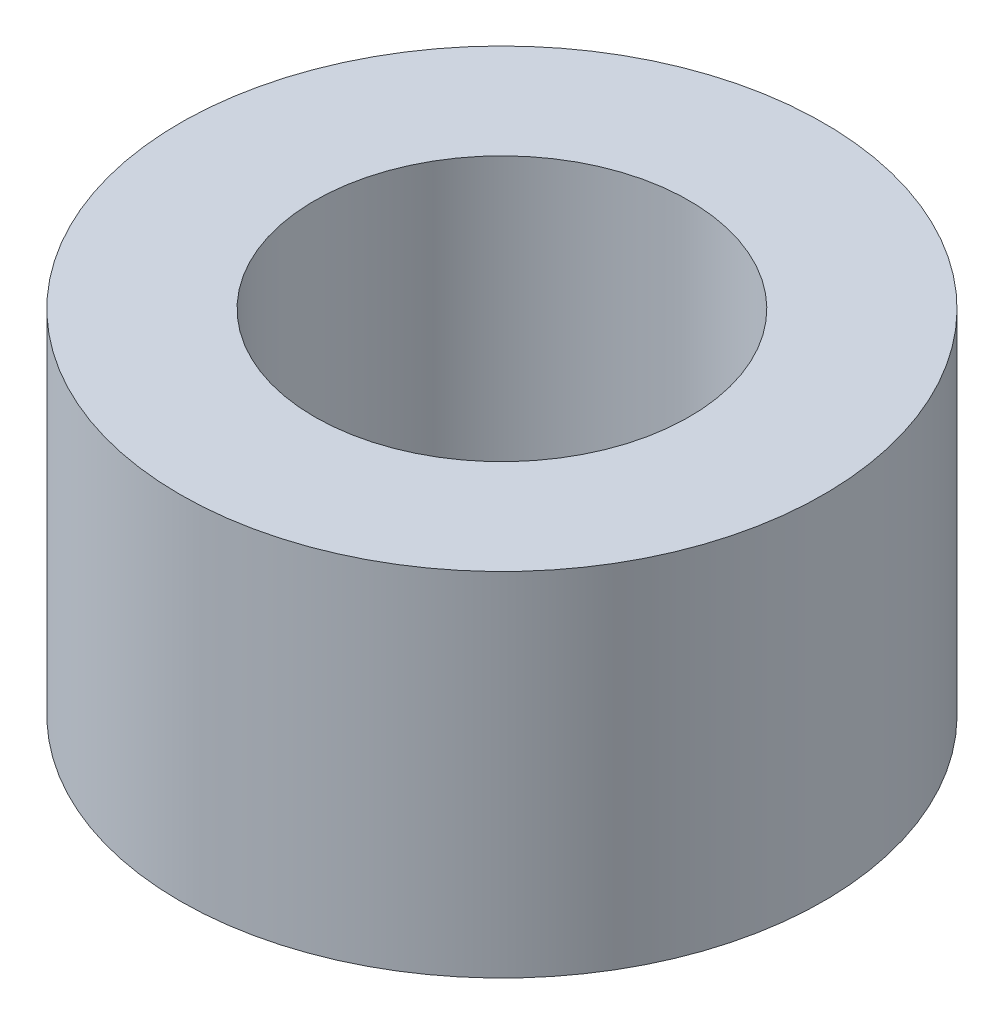
SolidWorks part; units mm, degrees
material "Brass"
ref_plane "Front" through (0, 0, 0) normal (0, 0, 1) x (1, 0, 0)
ref_plane "Top" through (0, 0, 0) normal (0, 1, 0) x (1, 0, 0)
ref_plane "Right" through (0, 0, 0) normal (1, 0, 0) x (0, 0, -1)
sketch "Sketch1" plane through (0, 0, 0) normal (0, 1, 0) x (1, 0, 0)
  circle A0 centre (0, 0) radius 5.8039
  dimension "D1" = 11.6078
extrude "Boss-Extrude1" add sketch "Sketch1" along normal blind 6.35
hole_wizard "1/4 Clearance Hole1" positions "Sketch2" profile "Sketch3" hole size "1/4" standard "ANSI Inch" end condition up to next
sketch "Sketch2" plane through (0, 6.35, 0) normal (0, 1, 0) x (1, 0, 0)
  point P0 (0, 0)
sketch "Sketch3" plane through (0, 6.35, 0) normal (1, 0, 0) x (0, 0, 1)
  line L0 (0, 0) -> (0, 6.35)
  line L1 (0, 6.35) -> (3.3782, 6.35)
  line L2 (3.3782, 6.35) -> (3.3782, 0)
  line L5 (3.3782, 0) -> (0, 0)
  line L11 (0, -6.35) -> (0, 107.95) construction
  dimension "Thru Hole Dia." = 6.7564
  dimension "Thru Hole Depth" = 6.35
